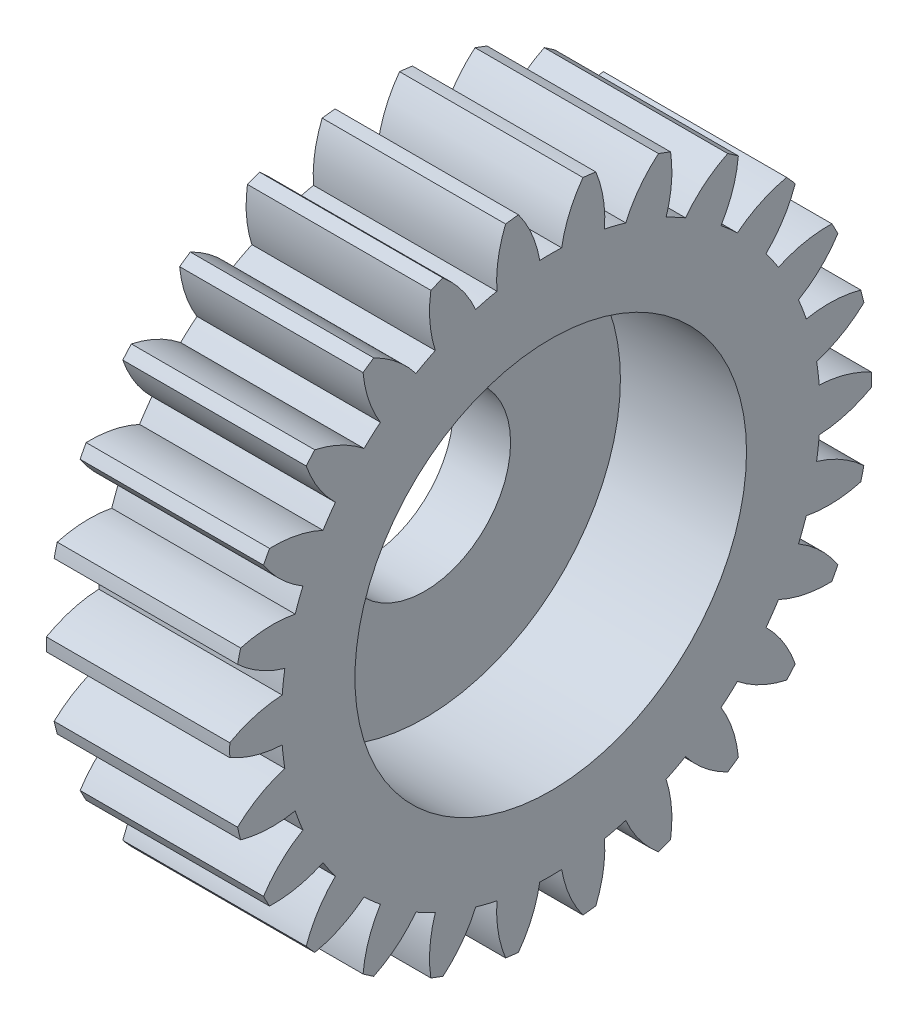
SolidWorks part; units mm, degrees
ref_plane "Plane1" through (0, 0, 0) normal (0, 0, 1) x (1, 0, 0)
ref_plane "Plane2" through (0, 0, 0) normal (0, 1, 0) x (1, 0, 0)
ref_plane "Plane3" through (0, 0, 0) normal (1, 0, 0) x (0, 0, -1)
other "Configuration Table"
sketch "HoldingSke" plane through (0, 0, 0) normal (0, 1, 0) x (1, 0, 0)
  line L0 (0, 0) -> (0.8988, -0.4384)
  line L1 (-15, 0) -> (100, 0) construction
  line L2 (0, 0) -> (-2.1039, 2.3779)
  line L3 (0, 0) -> (-11.863, 4.5341)
  line L4 (0, 0) -> (7.762, 3.7858)
  line L5 (0, 0) -> (-46.8476, -17.4728)
  line L6 (0, 0) -> (-8.2896, -5.593)
  line L7 (-2.1039, 2.3779) -> (8.6586, 51.2059)
  line L8 (-76.2, 54.61) -> (-76.1, 54.61)
  line L9 (-71.009, 38.7566) -> (-53.1078, 45.2721)
  line L10 (-76.2, 71.12) -> (104.1128, 71.12)
  line L11 (0, 0) -> (-10, 0)
  line L12 (-76.2, 101.6) -> (-76.162, 101.6)
  line L13 (24.9733, 27.94) -> (52.9518, 28.4284)
  line L14 (24.9733, 27.94) -> (24.9743, 27.94)
  line L15 (24.9733, 27.94) -> (100.4006, 29.5858)
  line L16 (-63.627, -1) -> (-12.827, -1)
  circle A0 centre (0, 0) radius 0.4
  circle A1 centre (0, 0) radius 11.749
  circle A2 centre (0, 0) radius 37.5
  circle A3 centre (0, 0) radius 0.4
  dimension "MHD" = 23.498
  dimension "Hub_dia" = 75
  dimension "Bore" = 0.8
  dimension "MBD" = 0.8
  dimension "Num_teeth" = 26
  dimension "Pitch" = 1
  dimension "Overall_len" = 50
  dimension "Show_teeth" = 26
  dimension "Thickness" = 10
  dimension "OAL" = 50.0001
  dimension "T_dim" = 0.1
  dimension "Ap" = 20
  dimension "H" = 19.05
  dimension "Pitch_radius" = 180.3128
  dimension "Width" = 10
  dimension "Backlash" = 0.038
  dimension "Addendum_fac" = 1
  dimension "Dedendum_fac" = 1.25
  dimension "Clearance_fac" = 0.25
  dimension "Dedendum_add" = 0.001
  dimension "Module" = 1
sketch "BasProSke" plane through (0, 0, 0) normal (0, 1, 0) x (1, 0, 0)
  line L0 (-10, 0) -> (60, 0) construction
  line L1 (0, 0) -> (0, 14)
  line L2 (0, 0) -> (10, 0)
  line L3 (10, 0) -> (10, 14)
  line L4 (10, 14) -> (0, 14)
  dimension "Thickness" = 10
  dimension "Diameter" = 28
revolve "Base-Revolve" add sketch "BasProSke" angle 360 about L0
sketch "TooCutSke" plane through (0, 0, 0) normal (1, 0, 0) x (0, 0, -1)
  line L1 (0, 0) -> (0, 107) construction
  line L2 (0, 0) -> (-0.8514, 12.9721) construction
  line L3 (0, 0) -> (-3.1292, 25.771) construction
  line L4 (-0.8514, 12.9721) -> (-1.5646, 12.8855) construction
  arc A0 (0.477, 11.7393) -> (-0.477, 11.7393) centre (0, 0) ccw
  arc A1 (1.4241, 13.9529) -> (-1.4241, 13.9529) centre (0, 0) ccw
  circle A2 centre (0, 0) radius 13 construction
  circle A3 centre (0, 0) radius 12.216 construction
  arc A4 (-0.477, 11.7393) -> (-1.4241, 13.9529) centre (-5.6014, 10.8561) ccw
  arc A5 (1.4241, 13.9529) -> (0.477, 11.7393) centre (5.6014, 10.8561) ccw
  dimension "Root_dia" = 23.498
  dimension "Overcut_dia" = 28.0508
  dimension "Pitch_dia" = 26
  dimension "Base_dia" = 24.432
  dimension "Flank_rad" = 5.2
  dimension "Half_ang" = 6.923
  dimension "Half_CT" = 0.7184
extrude "ToothCut" cut sketch "TooCutSke" along normal through all
fillet "Breaks" [suppressed] radius 0.02
fillet "RootFillets" [suppressed] radius 0.251
pattern_circular "TeethCuts" count 26 every 13.846 about axis through (-10, 0, 0) along (1, 0, 0) of "ToothCut", "RootFillets", "Breaks"
sketch "HubNeaOneSke" plane through (0, 0, 0) normal (-1, 0, 0) x (0, 0, 1)
  circle A0 centre (0, 0) radius 11.749
  dimension "Diameter" = 23.498
extrude "HubNearOne" [suppressed] add sketch "HubNeaOneSke" along normal blind 40.0001
sketch "HubNeaBotSke" plane through (0, 0, 0) normal (-1, 0, 0) x (0, 0, 1)
  circle A0 centre (0, 0) radius 11.749
  dimension "Diameter" = 23.498
extrude "HubNearBoth" [suppressed] add sketch "HubNeaBotSke" along normal blind 20
ref_plane "FarPln" through (10, 0, 0) normal (1, 0, 0) x (0, 0, -1)
sketch "HubFarSke" plane through (10, 0, 0) normal (1, 0, 0) x (0, 0, -1)
  circle A0 centre (0, 0) radius 11.749
  dimension "Diameter" = 23.498
extrude "HubFar" [suppressed] add sketch "HubFarSke" along normal blind 20
sketch "BorSke" plane through (0, 0, 0) normal (1, 0, 0) x (0, 0, -1)
  circle A0 centre (0, 0) radius 0.4
  dimension "Diameter" = 0.8
extrude "Bore" cut sketch "BorSke" along normal mid plane 100.0001
sketch "KeySke" plane through (0, 0, 0) normal (1, 0, 0) x (0, 0, -1)
  line L0 (-0.05, 0) -> (-0.05, 0.5)
  line L1 (-0.05, 0.5) -> (0.05, 0.5)
  line L2 (0.05, 0.5) -> (0.05, 0)
  line L3 (0, 0) -> (0, 34) construction
  line L4 (-0.05, 0) -> (0.05, 0)
  dimension "Offset" = 0.5
  dimension "Width" = 0.1
extrude "Keyway" [suppressed] cut sketch "KeySke" along normal mid plane 100.0001
pattern_circular "Keyway2" [suppressed] count 2 every 90 about axis through (-10, 0, 0) along (1, 0, 0)
sketch "Sketch1" plane through (10, 0, 0) normal (1, 0, 0) x (0, 0, -1)
  circle A0 centre (0, 0) radius 8.54
  dimension "D1" = 17.08
extrude "Cut-Extrude1" cut sketch "Sketch1" against normal blind 5.5
sketch "Sketch2" plane through (4.5, 0, 0) normal (1, 0, 0) x (0, 0, -1)
  circle A0 centre (0, 0) radius 3.75
  dimension "D1" = 7.5
extrude "Cut-Extrude2" cut sketch "Sketch2" against normal through all
sketch "Sketch3" plane through (0, 0, 0) normal (-1, 0, 0) x (0, 0, 1)
  circle A0 centre (0, 0) radius 15.2948
extrude "Cut-Extrude3" cut sketch "Sketch3" against normal blind 2
equation "' \"Module@HoldingSke\" = 6.35"
equation "' \"Num_teeth@HoldingSke\" = 12"
equation "' \"Ap@HoldingSke\" =  20"
equation "' \"Ap@HoldingSke\" = 20"
equation "' \"Width@HoldingSke\" = 0.5 * 25.4"
equation "' \"Hub_dia@HoldingSke\"= 1 * 25.4"
equation "' \"Hub_dia@HoldingSke\" = 1 * 25.4"
equation "' \"Overall_len@HoldingSke\" = 1.0 * 25.4"
equation "' \"Bore@HoldingSke\" = 0.75 * 25.4"
equation "' \"T_dim@HoldingSke\" = 0.1 * 25.4"
equation "' \"Width@KeySke\" = 0.25 * 25.4"
equation "' \"Show_teeth@HoldingSke\" = 13"
equation "' \"Backlash@HoldingSke\" = 0.009 * 25.4"
equation "' \"Addendum_fac@HoldingSke\" = 1.0"
equation "' \"Dedendum_fac@HoldingSke\" = 1.25"
equation "' \"Dedendum_add@HoldingSke\" = 0.00005 * 25.4"
equation "' \"Clearance_fac@HoldingSke\" = 0.25"
equation "\"Pitch@HoldingSke\" = 1 / \"Module@HoldingSke\""
equation "\"Overcut_dia@TooCutSke\" = (\"Num_teeth@HoldingSke\" + 2 * \"Addendum_fac@HoldingSke\") / \"Pitch@HoldingSke\" + 0.002 * 25.4"
equation "\"Pitch_dia@TooCutSke\" = \"Num_teeth@HoldingSke\" / \"Pitch@HoldingSke\""
equation "\"Base_dia@TooCutSke\" = \"Num_teeth@HoldingSke\" / \"Pitch@HoldingSke\" * cos((\"Ap@HoldingSke\"  * 3.14159265 / 180))"
equation "\"Root_dia@TooCutSke\" = (\"Num_teeth@HoldingSke\" + 2) / \"Pitch@HoldingSke\" - 2 * (\"Addendum_fac@HoldingSke\" + \"Dedendum_fac@HoldingSke\") / \"Pitch@HoldingSke\" - \"Dedendum_add@HoldingSke\" * 2"
equation "\"Half_ang@TooCutSke\" = 180 / \"Num_teeth@HoldingSke\""
equation "\"Half_CT@TooCutSke\" = \"Num_teeth@HoldingSke\" / \"Pitch@HoldingSke\" * sin((3.14159265 / 2 / \"Num_teeth@HoldingSke\")) / 2 - 7 * \"Backlash@HoldingSke\" / 4"
equation "\"Flank_rad@TooCutSke\" = \"Num_teeth@HoldingSke\" / \"Pitch@HoldingSke\" / 5"
equation "\"Radius@RootFillets\" = \"Clearance_fac@HoldingSke\" / \"Pitch@HoldingSke\" + \"Dedendum_add@HoldingSke\""
equation "\"Break_rad@Breaks\" = 0.02 / \"Pitch@HoldingSke\""
equation "\"Thickness@HoldingSke\" = \"Width@HoldingSke\""
equation "\"OAL@HoldingSke\" = \"Thickness@HoldingSke\""
equation "\"MHD@HoldingSke\" = (\"Num_teeth@HoldingSke\" + 2) / \"Pitch@HoldingSke\" - 2 * (\"Addendum_fac@HoldingSke\" + \"Dedendum_fac@HoldingSke\")  / \"Pitch@HoldingSke\" - \"Dedendum_add@HoldingSke\" * 2"
equation "\"MBD@HoldingSke\" = (\"Num_teeth@HoldingSke\" + 2) / \"Pitch@HoldingSke\" - 2 * (\"Addendum_fac@HoldingSke\" + \"Dedendum_fac@HoldingSke\")  / \"Pitch@HoldingSke\" - \"Dedendum_add@HoldingSke\" * 2 - 0.002 * 25.4"
equation "\"MHD@HoldingSke\" = ((sgn( \"MHD@HoldingSke\" - \"Hub_dia@HoldingSke\" )-1)*( \"MHD@HoldingSke\" - \"Hub_dia@HoldingSke\" ))/-2+ \"Hub_dia@HoldingSke\""
equation "\"MBD@HoldingSke\" = ((sgn( \"MBD@HoldingSke\" - \"Bore@HoldingSke\" )-1)*( \"MBD@HoldingSke\" - \"Bore@HoldingSke\" ))/-2+ \"Bore@HoldingSke\""
equation "\"OAL@HoldingSke\" = ((sgn( \"OAL@HoldingSke\" - \"Overall_len@HoldingSke\" )+1)*( \"OAL@HoldingSke\" - \"Overall_len@HoldingSke\" ))/2 + \"Overall_len@HoldingSke\" + 0.000002 * 25.4"
equation "\"Num_teeth@TeethCuts\" = int( \"Show_teeth@HoldingSke\" ) + 1"
equation "\"Num_teeth@TeethCuts\" = ((sgn( \"Num_teeth@TeethCuts\" - \"Num_teeth@HoldingSke\" )-1)*( \"Num_teeth@TeethCuts\" - \"Num_teeth@HoldingSke\" ))/-2+ \"Num_teeth@HoldingSke\""
equation "\"Num_teeth@TeethCuts\" = ((sgn( \"Num_teeth@TeethCuts\" - 2.0)+1)*( \"Num_teeth@TeethCuts\" - 2.0))/2 +2.0"
equation "\"Angle@TeethCuts\" = 360.0 / \"Num_teeth@HoldingSke\""
equation "\"Diameter@BasProSke\" = (\"Num_teeth@HoldingSke\" + 2 * \"Addendum_fac@HoldingSke\") / \"Pitch@HoldingSke\""
equation "\"Thickness@BasProSke\"  = \"Thickness@HoldingSke\""
equation "' \"Fillet_rad@BasProSke\" =  \"Thickness@HoldingSke\" * 0.05"
equation "' \"Fillet_rad@BasProSke\" = \"Thickness@HoldingSke\" * 0.05"
equation "\"MHD@HoldingSke\" = ((sgn( \"MHD@HoldingSke\" - \"Root_dia@TooCutSke\" )-1)*( \"MHD@HoldingSke\" - \"Root_dia@TooCutSke\" ))/-2+ \"Root_dia@TooCutSke\""
equation "\"Diameter@HubNeaOneSke\" = \"MHD@HoldingSke\""
equation "\"Length@HubNearOne\" = \"OAL@HoldingSke\" - \"Thickness@BasProSke\""
equation "\"Diameter@HubNeaBotSke\" = \"MHD@HoldingSke\""
equation "\"Length@HubNearBoth\" = ( \"OAL@HoldingSke\" - \"Thickness@BasProSke\" ) / 2.0"
equation "\"Thickness@FarPln\" = \"Thickness@BasProSke\""
equation "\"Diameter@HubFarSke\" = \"MHD@HoldingSke\""
equation "\"Length@HubFar\" = ( \"OAL@HoldingSke\" - \"Thickness@BasProSke\" ) / 2.0"
equation "\"Diameter@BorSke\" = \"MBD@HoldingSke\""
equation "\"D1@Bore\" = \"OAL@HoldingSke\" * 2.0"
equation "\"D1@Keyway\" = \"OAL@HoldingSke\" * 2.0"
equation "\"Offset@KeySke\" = \"T_dim@HoldingSke\" + \"MBD@HoldingSke\" / 2.0"
